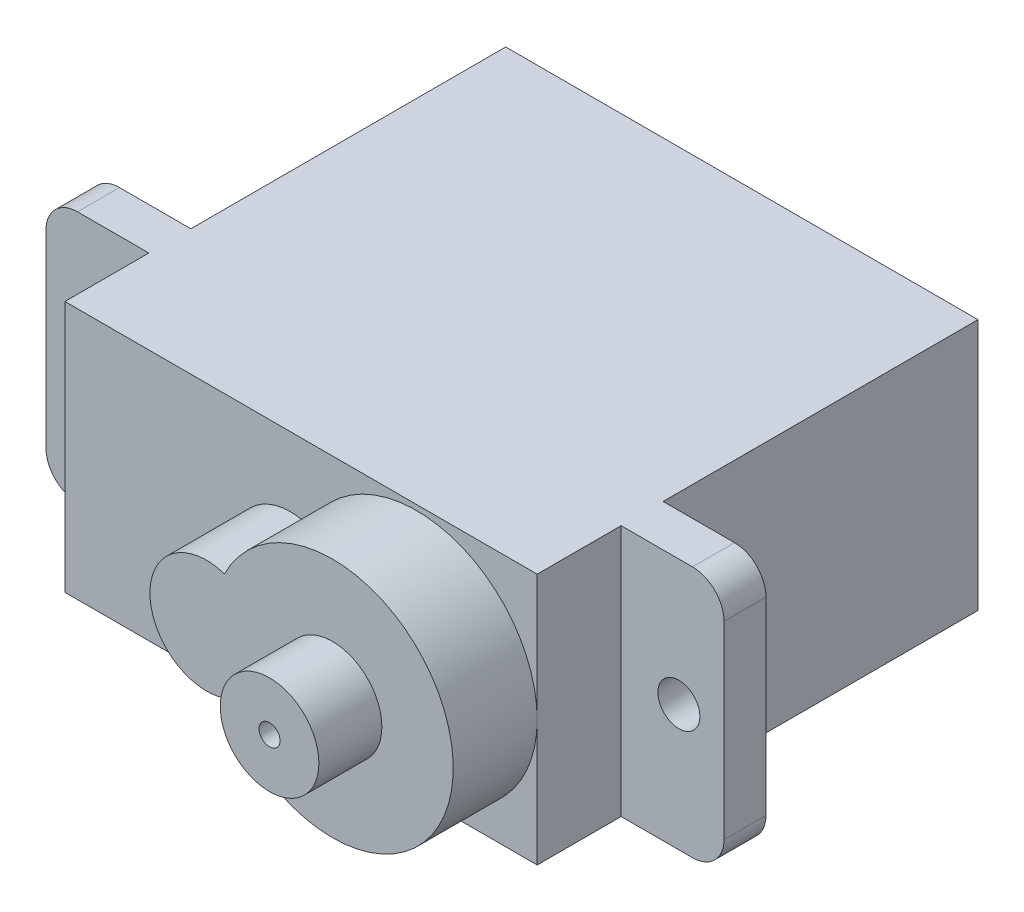
SolidWorks part; units mm, degrees
ref_plane "Plano frontal" through (0, 0, 0) normal (0, 0, 1) x (1, 0, 0)
ref_plane "Plano superior" through (0, 0, 0) normal (0, 1, 0) x (1, 0, 0)
ref_plane "Plano direito" through (0, 0, 0) normal (1, 0, 0) x (0, 0, -1)
sketch "Esboço4" plane through (0, 0, 0) normal (0, 1, 0) x (1, 0, 0)
  line L0 (0, 10.5) -> (0, -10.5) construction
  line L1 (-11.25, -10.5) -> (11.25, -10.5)
  line L28 (11.25, 10.5) -> (-11.25, 10.5)
  line L29 (-11.25, 10.5) -> (-11.25, -4.5)
  line L30 (-11.25, -4.5) -> (-16.15, -4.5)
  line L31 (-16.15, -4.5) -> (-16.15, -6.5)
  line L32 (-16.15, -6.5) -> (-11.25, -6.5)
  line L33 (-11.25, -6.5) -> (-11.25, -10.5)
  line L37 (11.25, -10.5) -> (11.25, -6.5)
  line L38 (11.25, -6.5) -> (16.15, -6.5)
  line L39 (16.15, -6.5) -> (16.15, -4.5)
  line L40 (16.15, -4.5) -> (11.25, -4.5)
  line L41 (11.25, -4.5) -> (11.25, 10.5)
  dimension "D1" = 22.5
  dimension "D2" = 15
  dimension "D3" = 32.3
  dimension "D6" = 4
  dimension "D7" = 2
extrude "Ressalto-extrusão4" add sketch "Esboço4" along normal mid plane 12
sketch "Esboço8" plane through (0, 0, 10.5) normal (0, 0, 1) x (1, 0, 0)
  line L3 (11.25, 6) -> (11.25, -6) construction
  circle A0 centre (5.5, 0) radius 5.75
  dimension "D1" = 11.5
extrude "Ressalto-extrusão7" add sketch "Esboço8" along normal blind 4
sketch "Esboço9" plane through (0, 0, 14.5) normal (0, 0, 1) x (1, 0, 0)
  circle A0 centre (5.5, 0) radius 2.35
  circle A1 centre (5.5, 0) radius 0.5
  dimension "D1" = 4.7
  dimension "D2" = 1
extrude "Ressalto-extrusão8" add sketch "Esboço9" along normal blind 3
sketch "Esboço10" plane through (0, 0, 10.5) normal (0, 0, 1) x (1, 0, 0)
  circle A0 centre (-0.5, 0) radius 2.7
  circle A2 centre (5.5, 0) radius 0.5 construction
  dimension "D1" = 5.4
  dimension "D2" = 6
extrude "Ressalto-extrusão9" add sketch "Esboço10" along normal up to surface (4 mm away) up to face at (11.25, 0, 14.5)
sketch "Esboço12" plane through (0, 0, 6.5) normal (0, 0, 1) x (1, 0, 0)
  line L0 (-14, 0) -> (14, 0) construction
  circle A0 centre (-14, 0) radius 1
  circle A1 centre (14, 0) radius 1
  dimension "D2" = 2
  dimension "D1" = 28
extrude "Corte-extrusão1" cut sketch "Esboço12" against normal through all
fillet "Filete1" radius 1.5 4 edges at (-16.15, 6, 5.5) (-16.15, -6, 5.5) (16.15, 6, 5.5) (16.15, -6, 5.5)
